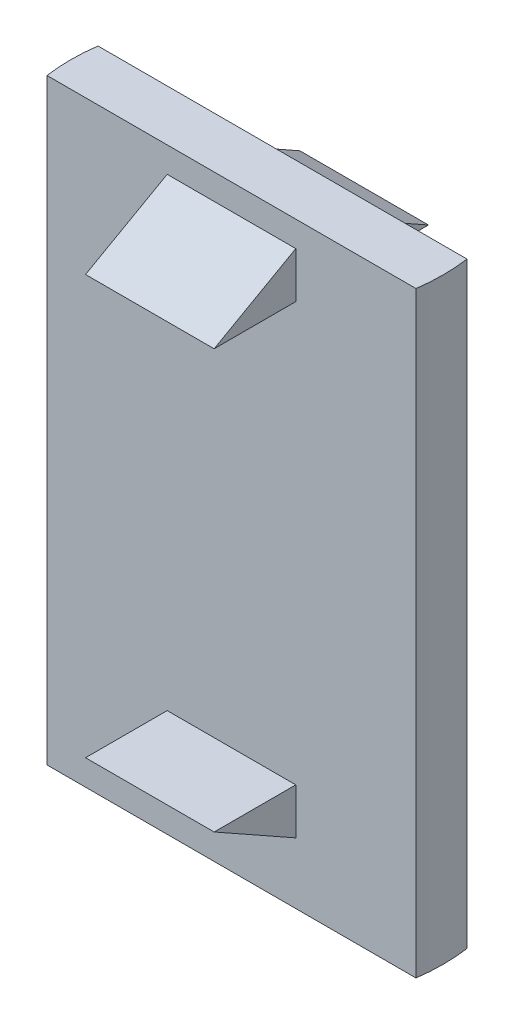
SolidWorks part; units mm, degrees
ref_plane "Front Plane" through (0, 0, 0) normal (0, 0, 1) x (1, 0, 0)
ref_plane "Top Plane" through (0, 0, 0) normal (0, 1, 0) x (1, 0, 0)
ref_plane "Right Plane" through (0, 0, 0) normal (1, 0, 0) x (0, 0, -1)
sketch "Sketch1" plane through (0, 0, 0) normal (0, 0, 1) x (1, 0, 0)
  line L1 (49.53, -180.34) -> (-49.53, -180.34)
  line L2 (49.53, -180.34) -> (49.53, 180.34)
  line L3 (49.53, 180.34) -> (-49.53, 180.34)
  line L4 (-49.53, -180.34) -> (-49.53, 180.34)
  line L5 (49.53, -180.34) -> (-49.53, 180.34) construction
  line L6 (49.53, 180.34) -> (-49.53, -180.34) construction
  point P0 (0, 0)
  dimension "D1" = 360.68
  dimension "D2" = 99.06
extrude "Boss-Extrude1" add sketch "Sketch1" along normal blind 12.7
sketch "Sketch2" plane through (0, 0, 12.7) normal (0, 0, 1) x (1, 0, 0)
  line L0 (0, 180.34) -> (0, -230.2299) construction
  line L2 (49.53, 180.34) -> (-49.53, 180.34) construction
  line L4 (-49.53, 0) -> (49.53, 0) construction
  line L10 (27.94, -25.4) -> (-27.94, -25.4)
  line L15 (27.94, -25.4) -> (27.94, 177.8)
  line L16 (27.94, 177.8) -> (-27.94, 177.8)
  line L17 (49.53, -180.34) -> (49.53, 180.34) construction
  line L18 (-27.94, -25.4) -> (-27.94, 177.8)
  line L19 (27.94, -25.4) -> (-27.94, 177.8) construction
  line L20 (27.94, 177.8) -> (-27.94, -25.4) construction
  line L21 (27.94, -12.7) -> (-27.94, -12.7)
  line L22 (27.94, -12.7) -> (27.94, 165.1)
  line L23 (27.94, 165.1) -> (-27.94, 165.1)
  line L24 (-27.94, -12.7) -> (-27.94, 165.1)
  line L25 (27.94, -12.7) -> (-27.94, 165.1) construction
  line L26 (27.94, 165.1) -> (-27.94, -12.7) construction
  point P1 (0, 76.2)
  point P15 (0, 76.2)
  dimension "D1" = 76.2
  dimension "D2" = 203.2
  dimension "D3" = 177.8
  dimension "D4" = 55.88
sketch "Sketch3" plane through (0, 0, 0) normal (0, 0, -1) x (-1, 0, 0)
  line L0 (0, -180.34) -> (0, 180.34) construction
  line L1 (-49.53, 180.34) -> (49.53, 180.34) construction
  line L2 (49.53, 0) -> (-49.53, 0) construction
  line L3 (-49.53, -180.34) -> (-49.53, 180.34) construction
  line L11 (16.002, -165.1) -> (-16.002, -165.1)
  line L12 (16.002, -165.1) -> (16.002, -38.1)
  line L13 (16.002, -38.1) -> (-16.002, -38.1)
  line L14 (-16.002, -165.1) -> (-16.002, -38.1)
  line L15 (16.002, -165.1) -> (-16.002, -38.1) construction
  line L16 (16.002, -38.1) -> (-16.002, -165.1) construction
  line L23 (16.002, -153.67) -> (-16.002, -153.67)
  line L24 (16.002, -153.67) -> (16.002, -49.53)
  line L25 (16.002, -49.53) -> (-16.002, -49.53)
  line L26 (-16.002, -153.67) -> (-16.002, -49.53)
  line L27 (16.002, -153.67) -> (-16.002, -49.53) construction
  line L28 (16.002, -49.53) -> (-16.002, -153.67) construction
  point P6 (0, 0)
  point P12 (0, 0)
  point P17 (0, -101.6)
  point P26 (0, -101.6)
  dimension "D1" = 127
  dimension "D2" = 32.004
  dimension "D5" = 101.6
  dimension "D7" = 104.14
extrude "Boss-Extrude3" add sketch "Sketch3" along normal blind 20.32 contours L25 L12 L13 L14 | L12 L23 L14 L11
extrude "Boss-Extrude4" add sketch "Sketch2" along normal mid plane 15.24 contours L23 L15 L16 L18 | L15 L21 L18 L10
ref_plane "Plane2" through (0, 0, 6.35) normal (0, 0, 1) x (1, 0, 0)
mirror "Mirror1" about plane through (0, 0, 6.35) normal (0, 0, 1) of "Boss-Extrude3"
sketch "Sketch5" plane through (0, 0, 0) normal (1, 0, 0) x (0, 0, -1)
  line L0 (-12.7, -180.34) -> (0, -180.34) construction
  line L1 (-12.7, 180.34) -> (0, 180.34) construction
  line L2 (-12.7, 180.34) -> (-12.7, -180.34) construction
  line L3 (-12.7, -180.34) -> (0, -180.34) construction
  line L5 (-20.32, 165.1) -> (-12.7, 165.1) construction
  line L6 (20.32, -153.67) -> (0, -153.67) construction
  line L7 (20.32, -153.67) -> (20.32, -165.1) construction
  line L8 (20.32, -165.1) -> (0, -165.1) construction
  line L9 (0, -153.67) -> (0, -165.1) construction
  line L10 (-33.02, -153.67) -> (-12.7, -153.67) construction
  line L11 (-33.02, -153.67) -> (-33.02, -165.1) construction
  line L12 (-33.02, -165.1) -> (-12.7, -165.1) construction
  line L13 (-12.7, -153.67) -> (-12.7, -165.1) construction
  line L14 (20.32, -38.1) -> (0, -38.1) construction
  line L15 (20.32, -38.1) -> (20.32, -49.53) construction
  line L16 (20.32, -49.53) -> (0, -49.53) construction
  line L17 (0, -38.1) -> (0, -49.53) construction
  line L18 (-33.02, -38.1) -> (-12.7, -38.1) construction
  line L19 (-33.02, -38.1) -> (-33.02, -49.53) construction
  line L20 (-33.02, -49.53) -> (-12.7, -49.53) construction
  line L21 (-12.7, -38.1) -> (-12.7, -49.53) construction
  line L25 (-12.7, -12.7) -> (-12.7, 0) construction
  line L26 (-20.32, 177.8) -> (-12.7, 177.8) construction
  line L27 (-20.32, 177.8) -> (-20.32, 165.1) construction
  line L28 (-20.32, 165.1) -> (-12.7, 165.1) construction
  line L29 (-12.7, 177.8) -> (-12.7, 165.1) construction
  line L30 (0, 180.34) -> (0, -180.34) construction
  line L31 (20.32, -153.67) -> (0, -165.1)
  line L32 (0, -165.1) -> (20.32, -165.1)
  line L33 (20.32, -165.1) -> (20.32, -153.67)
  line L34 (-33.02, -153.67) -> (-12.7, -165.1)
  line L35 (-12.7, -165.1) -> (-33.02, -165.1)
  line L36 (-33.02, -165.1) -> (-33.02, -153.67)
  line L37 (-33.02, -49.53) -> (-33.02, -38.1)
  line L38 (-33.02, -38.1) -> (-12.7, -38.1)
  line L39 (-12.7, -38.1) -> (-33.02, -49.53)
  line L40 (20.32, -49.53) -> (0, -38.1)
  line L41 (0, -38.1) -> (20.32, -38.1)
  line L42 (20.32, -38.1) -> (20.32, -49.53)
  line L46 (-12.7, 177.8) -> (-20.32, 165.1)
  line L47 (-20.32, 165.1) -> (-20.32, 177.8)
  line L48 (-20.32, 177.8) -> (-12.7, 177.8)
  line L49 (-12.7, -12.7) -> (-20.32, -12.7) construction
  line L50 (-20.32, -12.7) -> (-20.32, -25.4) construction
  line L51 (-20.32, -25.4) -> (-12.7, -25.4) construction
  line L52 (-20.32, -12.7) -> (-12.7, -25.4)
  line L53 (-12.7, -25.4) -> (-20.32, -25.4)
  line L54 (-20.32, -25.4) -> (-20.32, -12.7)
extrude "Cut-Extrude2" cut sketch "Sketch5" against normal mid plane 76.2
sketch "Sketch6" plane through (0, 180.34, 0) normal (0, 1, 0) x (1, 0, 0)
  line L0 (0, 0) -> (0, -12.7) construction
  line L1 (-49.53, -12.7) -> (49.53, -12.7) construction
  line L2 (-49.53, -12.7) -> (-49.53, 0) construction
  line L3 (-49.53, 0) -> (49.53, 0) construction
  line L4 (49.53, -12.7) -> (49.53, 0) construction
  line L5 (-49.53, -6.35) -> (49.53, -6.35) construction
  line L7 (25.4, -8.89) -> (-25.4, -8.89)
  line L8 (25.4, -8.89) -> (25.4, -3.81)
  line L9 (25.4, -3.81) -> (-25.4, -3.81)
  line L10 (-25.4, -8.89) -> (-25.4, -3.81)
  line L11 (25.4, -8.89) -> (-25.4, -3.81) construction
  line L12 (25.4, -3.81) -> (-25.4, -8.89) construction
  point P10 (0, -6.35)
  dimension "D1" = 5.08
  dimension "D2" = 50.8
extrude "Cut-Extrude3" cut sketch "Sketch6" against normal blind 2.54
mirror "Mirror2" about plane through (0, 0, 0) normal (0, 1, 0) of "Cut-Extrude3"
sketch "Sketch7" plane through (0, 180.34, 0) normal (0, 1, 0) x (1, 0, 0)
  line L0 (-49.53, -6.35) -> (49.53, -6.35) construction
  line L1 (-49.53, -12.7) -> (-49.53, 0) construction
  line L2 (49.53, -12.7) -> (49.53, 0) construction
  line L3 (0, 0) -> (0, -12.7) construction
  line L4 (-16.002, 0) -> (16.002, 0) construction
  line L5 (-27.94, -12.7) -> (27.94, -12.7) construction
  circle A0 centre (0, -6.35) radius 46.355
  circle A1 centre (0, -6.35) radius 50.8
  dimension "D1" = 92.71
  dimension "D2" = 101.6
extrude "Cut-Extrude4" cut sketch "Sketch7" against normal through all
sketch "Sketch9" plane through (0, 0, 0) normal (0, 0, 1) x (1, 0, 0)
  line L0 (-27.94, -25.4) -> (27.94, -25.4) construction
  line L1 (-77.6411, -31.75) -> (77.6411, -31.75)
  line L2 (-77.6411, -31.75) -> (-77.6411, 195.0971)
  line L3 (-77.6411, 195.0971) -> (77.6411, 195.0971)
  line L4 (77.6411, -31.75) -> (77.6411, 195.0971)
  dimension "D1" = 6.35
extrude "Cut-Extrude9" cut sketch "Sketch9" against normal mid plane 50.8
